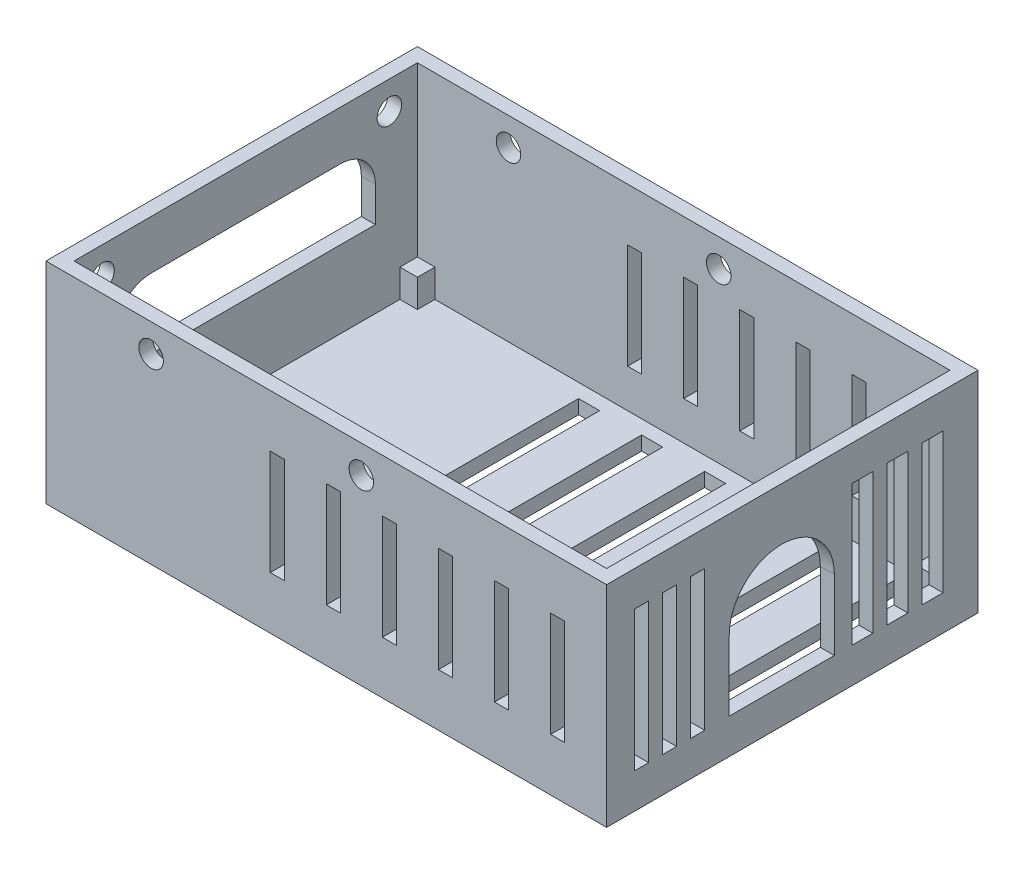
SolidWorks part; units mm, degrees
ref_plane "Front Plane" through (0, 0, 0) normal (0, 0, 1) x (1, 0, 0)
ref_plane "Top Plane" through (0, 0, 0) normal (0, 1, 0) x (1, 0, 0)
ref_plane "Right Plane" through (0, 0, 0) normal (1, 0, 0) x (0, 0, -1)
sketch "Sketch1" plane through (0, 0, 0) normal (0, 1, 0) x (1, 0, 0)
  line L1 (40, -26.5) -> (-40, -26.5)
  line L2 (40, -26.5) -> (40, 26.5)
  line L3 (40, 26.5) -> (-40, 26.5)
  line L4 (-40, -26.5) -> (-40, 26.5)
  line L5 (40, -26.5) -> (-40, 26.5) construction
  line L6 (40, 26.5) -> (-40, -26.5) construction
  point P0 (0, 0)
  dimension "D1" = 80
  dimension "D2" = 53
extrude "Boss-Extrude1" add sketch "Sketch1" along normal blind 30
sketch "Sketch2" plane through (0, 30, 0) normal (0, 1, 0) x (1, 0, 0)
  line L0 (40, 26.5) -> (-40, 26.5) construction
  line L1 (38, -24.5) -> (-38, -24.5)
  line L2 (38, -24.5) -> (38, 24.5)
  line L3 (38, 24.5) -> (-38, 24.5)
  line L4 (-38, -24.5) -> (-38, 24.5)
  line L5 (38, -24.5) -> (-38, 24.5) construction
  line L6 (38, 24.5) -> (-38, -24.5) construction
  line L7 (40, -26.5) -> (40, 26.5) construction
  point P0 (0, 0)
  dimension "D1" = 2
  dimension "D2" = 2
extrude "Cut-Extrude1" cut sketch "Sketch2" against normal blind 28
sketch "Sketch3" plane through (40, 0, 0) normal (1, 0, 0) x (0, 0, -1)
  line L2 (-26.5, 30) -> (-26.5, 0) construction
  line L3 (6, 15) -> (6, 5)
  line L4 (6, 5) -> (-9, 5)
  line L5 (-26.5, 0) -> (26.5, 0) construction
  line L6 (-9, 15) -> (-9, 5)
  line L8 (-1.5, 5) -> (-1.5, 31.1602) construction
  arc A0 (6, 15) -> (-9, 15) centre (-1.5, 15) ccw
  dimension "D3" = 7.5
  dimension "D1" = 15
  dimension "D2" = 10
  dimension "D4" = 25
  dimension "D5" = 5
extrude "Cut-Extrude2" cut sketch "Sketch3" against normal blind 6
sketch "Sketch4" plane through (-40, 0, 0) normal (-1, 0, 0) x (0, 0, 1)
  line L2 (0, 0) -> (0, 30) construction
  line L3 (-26.5, 0) -> (26.5, 0) construction
  line L4 (-26.5, 30) -> (26.5, 30) construction
  line L5 (0, 13) -> (0, 23) construction
  line L6 (-18.5, 23) -> (18.5, 23)
  line L7 (-18.5, 23) -> (-18.5, 13)
  line L8 (-18.5, 13) -> (18.5, 13)
  line L9 (18.5, 23) -> (18.5, 13)
  dimension "D1" = 23
  dimension "D3" = 13
  dimension "D2" = 37
extrude "Cut-Extrude3" cut sketch "Sketch4" against normal blind 6
sketch "Sketch5" plane through (0, 2, 0) normal (0, 1, 0) x (1, 0, 0)
  line L0 (0, 0) -> (-10, 0) construction
  line L1 (38, 24.5) -> (35.5, 24.5)
  line L2 (38, 24.5) -> (38, 22)
  line L3 (38, 22) -> (35.5, 22)
  line L4 (35.5, 24.5) -> (35.5, 22)
  line L5 (0, 0) -> (0, -10) construction
  line L6 (35.5, -24.5) -> (35.5, -22)
  line L7 (38, -22) -> (35.5, -22)
  line L8 (38, -24.5) -> (38, -22)
  line L9 (38, -24.5) -> (35.5, -24.5)
  line L10 (-38, -24.5) -> (-35.5, -24.5)
  line L11 (-38, -24.5) -> (-38, -22)
  line L12 (-38, -22) -> (-35.5, -22)
  line L13 (-35.5, -24.5) -> (-35.5, -22)
  line L14 (-35.5, 24.5) -> (-35.5, 22)
  line L15 (-38, 22) -> (-35.5, 22)
  line L16 (-38, 24.5) -> (-38, 22)
  line L17 (-38, 24.5) -> (-35.5, 24.5)
  line L18 (0, -24.5) -> (0, 24.5) construction
  line L19 (-38, -24.5) -> (38, -24.5) construction
  line L20 (38, 24.5) -> (-38, 24.5) construction
  dimension "D1" = 2.5
extrude "Standoffs" add sketch "Sketch5" along normal blind 4
fillet "Fillet3" radius 5 1 edges at (-39, 23, -18.5)
fillet "Fillet4" radius 5 1 edges at (-39, 23, 18.5)
sketch "Sketch6" plane through (0, 0, 0) normal (0, -1, 0) x (1, 0, 0)
  line L0 (40, 0) -> (37, 0) construction
  line L1 (32, -22.5) -> (35, -22.5)
  line L2 (32, -22.5) -> (32, 22.5)
  line L3 (32, 22.5) -> (35, 22.5)
  line L4 (35, -22.5) -> (35, 22.5)
  line L5 (32, -22.5) -> (35, 22.5) construction
  line L6 (32, 22.5) -> (35, -22.5) construction
  line L7 (29, -26.5) -> (29, 26.5) construction
  line L8 (40, -26.5) -> (-40, -26.5) construction
  line L9 (-40, 26.5) -> (40, 26.5) construction
  line L10 (26, -22.5) -> (23, -22.5)
  line L11 (26, 22.5) -> (23, -22.5) construction
  line L12 (26, -22.5) -> (23, 22.5) construction
  line L13 (23, -22.5) -> (23, 22.5)
  line L14 (26, 22.5) -> (23, 22.5)
  line L15 (26, -22.5) -> (26, 22.5)
  line L16 (20, -26.5) -> (20, 26.5) construction
  line L17 (14, -22.5) -> (17, 22.5) construction
  line L18 (14, 22.5) -> (17, -22.5) construction
  line L19 (8, 22.5) -> (5, -22.5) construction
  line L20 (8, -22.5) -> (5, 22.5) construction
  line L21 (0, 0) -> (3, 0) construction
  line L22 (14, -22.5) -> (14, 22.5)
  line L23 (14, 22.5) -> (17, 22.5)
  line L24 (17, -22.5) -> (17, 22.5)
  line L25 (40, 26.5) -> (40, -26.5) construction
  line L26 (14, -22.5) -> (17, -22.5)
  line L27 (5, -22.5) -> (5, 22.5)
  line L28 (8, 22.5) -> (5, 22.5)
  line L29 (8, -22.5) -> (8, 22.5)
  line L30 (8, -22.5) -> (5, -22.5)
  line L31 (2, -26.5) -> (2, 26.5) construction
  line L32 (4, 0) -> (1, 0) construction
  line L33 (-4, -22.5) -> (-1, 22.5) construction
  line L34 (-4, 22.5) -> (-1, -22.5) construction
  line L35 (-10, 22.5) -> (-13, -22.5) construction
  line L36 (-10, -22.5) -> (-13, 22.5) construction
  line L37 (-4, -22.5) -> (-1, -22.5)
  line L38 (-4, -22.5) -> (-4, 22.5)
  line L39 (-4, 22.5) -> (-1, 22.5)
  line L40 (-1, -22.5) -> (-1, 22.5)
  line L41 (-10, -22.5) -> (-13, -22.5)
  line L42 (-13, -22.5) -> (-13, 22.5)
  line L43 (-10, 22.5) -> (-13, 22.5)
  line L44 (-10, -22.5) -> (-10, 22.5)
  point P0 (33.5, 0)
  point P32 (6.5, 0)
  point P45 (-2.5, 0)
  dimension "D1" = 3
  dimension "D2" = 45
  dimension "D3" = 5
  dimension "D4" = 3
  dimension "D5" = 3
  dimension "D6" = 3
extrude "Bottom Grill" cut sketch "Sketch6" against normal up to surface (2 mm away) up to face at (0, 2, 0)
sketch "Sketch7" plane through (0, 0, -26.5) normal (0, 0, -1) x (-1, 0, 0)
  line L0 (-40, 30) -> (-40, 0) construction
  line L1 (-34, 7.5) -> (-32, 7.5)
  line L2 (-34, 7.5) -> (-34, 22.5)
  line L3 (-34, 22.5) -> (-32, 22.5)
  line L4 (-32, 7.5) -> (-32, 22.5)
  line L5 (-34, 7.5) -> (-32, 22.5) construction
  line L6 (-34, 22.5) -> (-32, 7.5) construction
  line L7 (-40, 15) -> (-37.7615, 15) construction
  line L8 (-29, 30) -> (-29, 0) construction
  line L9 (-40, 30) -> (40, 30) construction
  line L10 (-40, 0) -> (40, 0) construction
  line L11 (-24, 22.5) -> (-26, 22.5)
  line L12 (-26, 7.5) -> (-26, 22.5)
  line L13 (-24, 7.5) -> (-26, 7.5)
  line L14 (-24, 7.5) -> (-24, 22.5)
  line L15 (-21, 30) -> (-21, 0) construction
  line L16 (-2, 15) -> (-4.2385, 15) construction
  line L17 (-8, 22.5) -> (-10, 7.5) construction
  line L18 (-8, 7.5) -> (-10, 22.5) construction
  line L19 (-18, 7.5) -> (-18, 22.5)
  line L20 (-18, 7.5) -> (-16, 7.5)
  line L21 (-16, 7.5) -> (-16, 22.5)
  line L22 (-18, 22.5) -> (-16, 22.5)
  line L23 (-10, 7.5) -> (-10, 22.5)
  line L24 (-8, 22.5) -> (-10, 22.5)
  line L25 (-8, 7.5) -> (-8, 22.5)
  line L26 (-8, 7.5) -> (-10, 7.5)
  line L27 (-5, 30) -> (-5, 0) construction
  line L28 (-2, 7.5) -> (0, 22.5) construction
  line L29 (-2, 22.5) -> (0, 7.5) construction
  line L30 (-2, 7.5) -> (0, 7.5)
  line L31 (-2, 7.5) -> (-2, 22.5)
  line L32 (-2, 22.5) -> (0, 22.5)
  line L33 (0, 7.5) -> (0, 22.5)
  line L34 (8, 22.5) -> (6, 22.5)
  line L35 (6, 7.5) -> (6, 22.5)
  line L36 (8, 7.5) -> (6, 7.5)
  line L37 (8, 7.5) -> (8, 22.5)
  point P0 (-33, 15)
  point P31 (-9, 15)
  point P42 (-1, 15)
  dimension "D1" = 2
  dimension "D2" = 15
  dimension "D3" = 6
  dimension "D4" = 3
  dimension "D5" = 3
  dimension "D6" = 3
extrude "Cut-Extrude5" cut sketch "Sketch7" against normal up to surface (53 mm away) up to face at (0, 15, 26.5)
sketch "Sketch8" plane through (0, 0, -26.5) normal (0, 0, -1) x (-1, 0, 0)
  line L0 (-40, 30) -> (40, 30) construction
  line L1 (40, 30) -> (40, 0) construction
  circle A0 centre (-5, 26) radius 1.75
  circle A1 centre (25, 26) radius 1.75
  dimension "D1" = 3.5
  dimension "D4" = 15
  dimension "D2" = 3
  dimension "D3" = 4
extrude "Cut-Extrude6" cut sketch "Sketch8" against normal up to surface (53 mm away)
sketch "Sketch9" plane through (-40, 0, 0) normal (-1, 0, 0) x (0, 0, 1)
  line L0 (-26.5, 30) -> (-26.5, 0) construction
  line L1 (-26.5, 30) -> (26.5, 30) construction
  line L2 (0, 30) -> (0, 0) construction
  line L3 (-26.5, 0) -> (26.5, 0) construction
  circle A0 centre (-20.5, 26) radius 1.75
  circle A1 centre (20.5, 26) radius 1.75
  dimension "D1" = 3.5
  dimension "D2" = 6
  dimension "D3" = 4
extrude "Cut-Extrude7" cut sketch "Sketch9" against normal up to surface (2 mm away) up to face at (-38, 18.3452, 0)
sketch "Sketch10" plane through (40, 0, 0) normal (1, 0, 0) x (0, 0, -1)
  line L0 (26.5, 30) -> (26.5, 0) construction
  line L1 (21.5, 5) -> (18.5, 5)
  line L2 (21.5, 5) -> (21.5, 25)
  line L3 (21.5, 25) -> (18.5, 25)
  line L4 (18.5, 5) -> (18.5, 25)
  line L5 (21.5, 5) -> (18.5, 25) construction
  line L6 (21.5, 25) -> (18.5, 5) construction
  line L7 (26.5, 15) -> (10.8459, 15) construction
  line L8 (17.5, 30) -> (17.5, 0) construction
  line L9 (-26.5, 30) -> (26.5, 30) construction
  line L10 (-26.5, 0) -> (26.5, 0) construction
  line L11 (12.5, 30) -> (12.5, 0) construction
  line L12 (13.5, 25) -> (16.5, 5) construction
  line L13 (13.5, 5) -> (16.5, 25) construction
  line L14 (16.5, 5) -> (16.5, 25)
  line L15 (13.5, 25) -> (16.5, 25)
  line L16 (13.5, 5) -> (13.5, 25)
  line L17 (13.5, 5) -> (16.5, 5)
  line L18 (11.5, 5) -> (8.5, 5)
  line L19 (8.5, 5) -> (8.5, 25)
  line L20 (11.5, 5) -> (11.5, 25)
  line L21 (11.5, 25) -> (8.5, 25)
  line L22 (0, 0) -> (0, 30) construction
  line L23 (-26.5, 15) -> (-15.6248, 15) construction
  line L24 (-20.5, 5) -> (-22.5, 5)
  line L25 (-20.5, 5) -> (-20.5, 25)
  line L26 (-20.5, 25) -> (-22.5, 25)
  line L27 (-22.5, 5) -> (-22.5, 25)
  line L28 (-20.5, 5) -> (-22.5, 25) construction
  line L29 (-20.5, 25) -> (-22.5, 5) construction
  line L30 (-26.5, 30) -> (-26.5, 0) construction
  line L31 (-19.5, 30) -> (-19.5, 0) construction
  line L32 (-18.5, 5) -> (-16.5, 5)
  line L33 (-18.5, 5) -> (-18.5, 25)
  line L34 (-16.5, 5) -> (-16.5, 25)
  line L35 (-18.5, 25) -> (-16.5, 25)
  line L36 (-15.5, 30) -> (-15.5, 0) construction
  line L37 (-12.5, 5) -> (-14.5, 5)
  line L38 (-12.5, 5) -> (-12.5, 25)
  line L39 (-14.5, 5) -> (-14.5, 25)
  line L40 (-12.5, 25) -> (-14.5, 25)
  point P0 (20, 15)
  point P27 (-21.5, 15)
  dimension "D1" = 3
  dimension "D2" = 5
  dimension "D3" = 20
  dimension "D4" = 1
  dimension "D5" = 1
  dimension "D6" = 4
  dimension "D7" = 2
  dimension "D8" = 1
  dimension "D9" = 1
extrude "Cut-Extrude8" cut sketch "Sketch10" against normal up to surface (2 mm away) up to face at (38, 11.875, 1.5)
